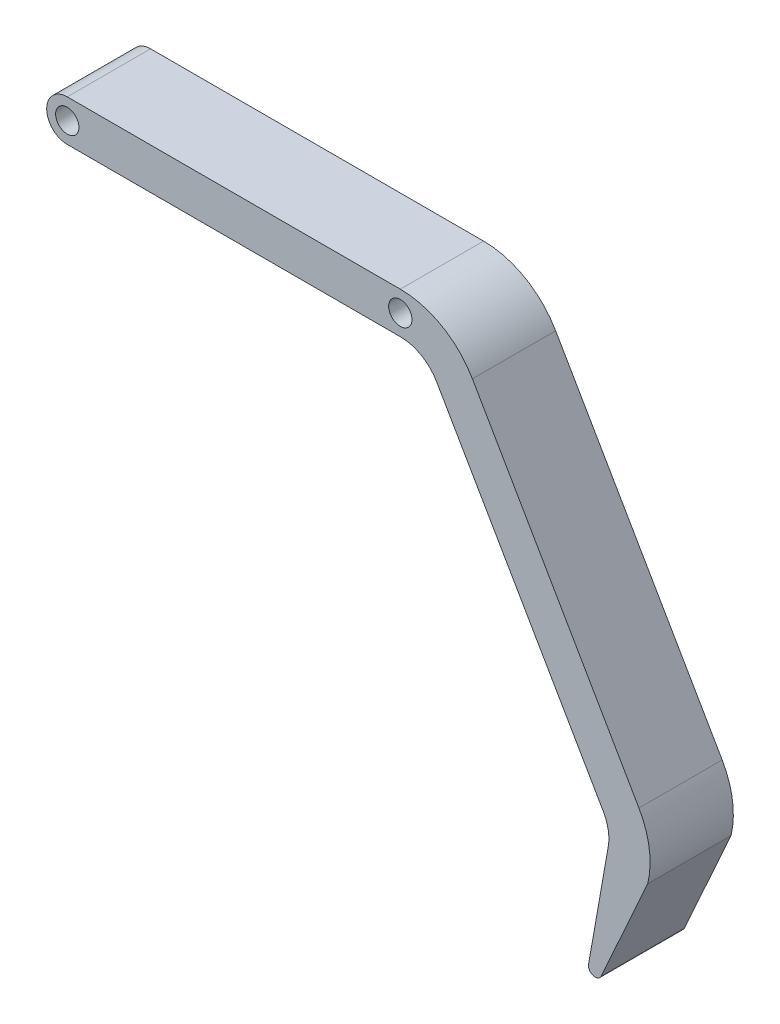
SolidWorks part; units mm, degrees
ref_plane "Front Plane" through (0, 0, 0) normal (0, 0, 1) x (1, 0, 0)
ref_plane "Top Plane" through (0, 0, 0) normal (0, 1, 0) x (1, 0, 0)
ref_plane "Right Plane" through (0, 0, 0) normal (1, 0, 0) x (0, 0, -1)
sketch "Sketch1" plane through (0, 0, 0) normal (0, 0, 1) x (1, 0, 0)
  line L0 (-25.4, 0) -> (25.4, 0)
  line L1 (-25.4, -6.2857) -> (25.4, -6.2857)
  line L2 (36.3985, -6.35) -> (61.7985, -50.3441)
  line L3 (30.955, -9.4928) -> (56.355, -53.4869)
  line L4 (57.1169, -57.8079) -> (52.7062, -82.822)
  line L5 (52.7062, -82.822) -> (63.1471, -59.6672)
  arc A0 (-25.4, 0) -> (-25.4, -6.2857) centre (-25.4, -3.1428) ccw
  arc A2 (25.4, -6.2857) -> (30.955, -9.4928) centre (25.4, -12.7) cw
  arc A3 (25.4, 0) -> (36.3985, -6.35) centre (25.4, -12.7) cw
  arc A4 (56.355, -53.4869) -> (57.1169, -57.8079) centre (50.8, -56.6941) cw
  arc A5 (61.7985, -50.3441) -> (63.1471, -59.6672) centre (50.8, -56.6941) cw
  dimension "D2" = 50.8
  dimension "D3" = 25.4
  dimension "D5" = 12.7
  dimension "D4" = 12.7
  dimension "D6" = 3.1428
  dimension "D7" = 120
  dimension "D1" = 50.8
  dimension "D8" = 140
extrude "Boss-Extrude1" add sketch "Sketch1" along normal blind 12.7
sketch "Sketch2" plane through (0, 0, 12.7) normal (0, 0, 1) x (1, 0, 0)
  circle A0 centre (-25.4, -3.1428) radius 1.778
  arc A1 (-25.4, 0) -> (-25.4, -6.2857) centre (-25.4, -3.1428) ccw construction
  dimension "D1" = 3.556
extrude "Cut-Extrude1" cut sketch "Sketch2" against normal through all
mirror "Mirror1" about plane through (0, 0, 0) normal (1, 0, 0) of "Cut-Extrude1"
fillet "Fillet1" radius 1.016 1 edges at (52.7062, -82.822, 6.35)
